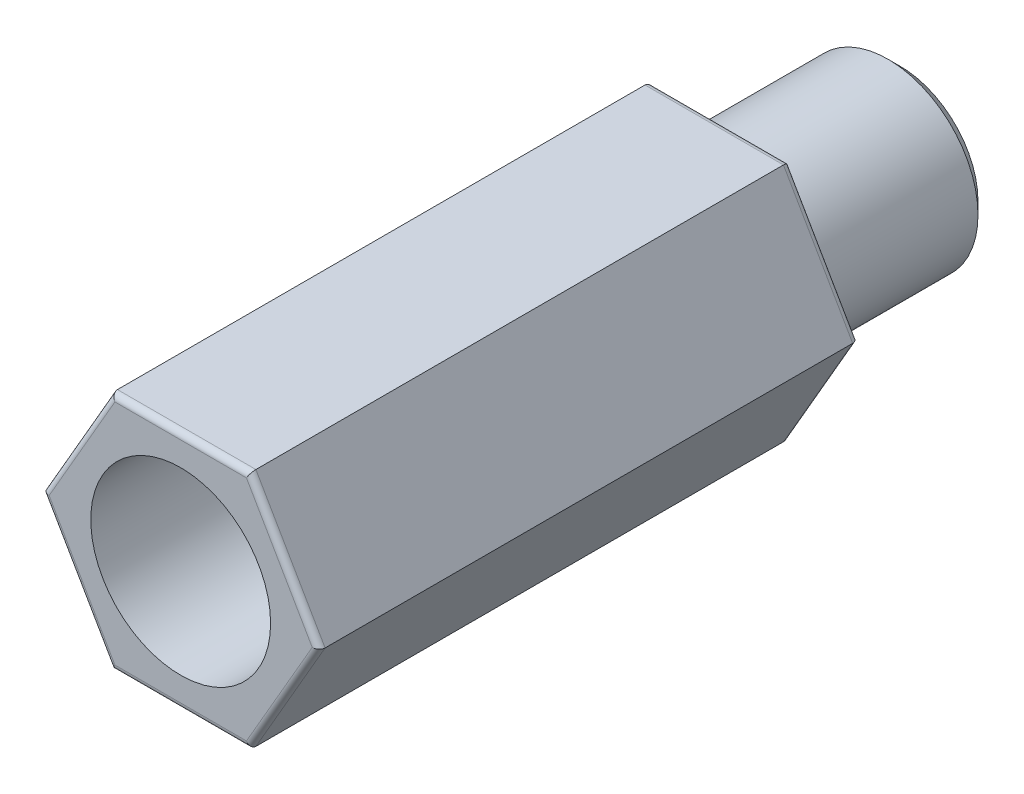
SolidWorks part; units mm, degrees
material "Mosaz"
ref_plane "Přední rovina" through (0, 0, 0) normal (0, 0, 1) x (1, 0, 0)
ref_plane "Horní rovina" through (0, 0, 0) normal (0, 1, 0) x (1, 0, 0)
ref_plane "Pravá rovina" through (0, 0, 0) normal (1, 0, 0) x (0, 0, -1)
sketch "Skica1" plane through (0, 0, 0) normal (0, 0, 1) x (1, 0, 0)
  circle A0 centre (0, 0) radius 1.5
  dimension "D1" = 3
extrude "Přidat vysunutím1" add sketch "Skica1" along normal blind 3
sketch "Skica2" plane through (0, 0, 3) normal (0, 0, 1) x (1, 0, 0)
  line L1 (2.3094, 0) -> (1.1547, 2)
  line L2 (1.1547, 2) -> (-1.1547, 2)
  line L3 (-1.1547, 2) -> (-2.3094, 0)
  line L4 (-2.3094, 0) -> (-1.1547, -2)
  line L5 (-1.1547, -2) -> (1.1547, -2)
  line L6 (1.1547, -2) -> (2.3094, 0)
  circle A0 centre (0, 0) radius 2 construction
  circle A1 centre (0, 0) radius 1.5
  dimension "D1" = 3
  dimension "D2" = 4
extrude "Přidat vysunutím2" add sketch "Skica2" along normal blind 9 separate body
chamfer "Zkosení1" distance 0.2 angle 45 1 edges at (1.5, 0, 0)
fillet "Zaoblit1" radius 0.1 13 edges at (1.7321, -1, 12) (0, -2, 12) (-1.7321, -1, 12) (-1.7321, 1, 12) (0, 2, 12) (1.7321, 1, 12) (1.5, 0, 3) (1.7321, 1, 3) (0, 2, 3) (-1.7321, 1, 3) (-1.7321, -1, 3) (0, -2, 3) (1.7321, -1, 3)
